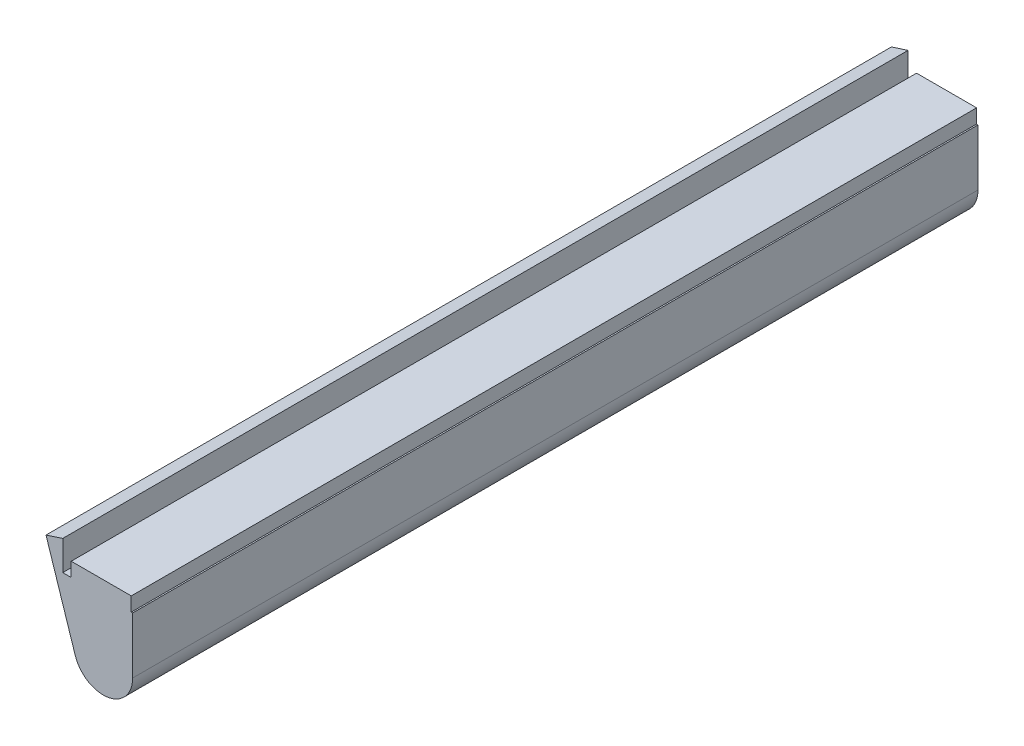
SolidWorks part; units mm, degrees
ref_plane "Front Plane" through (0, 0, 0) normal (0, 0, 1) x (1, 0, 0)
ref_plane "Top Plane" through (0, 0, 0) normal (0, 1, 0) x (1, 0, 0)
ref_plane "Right Plane" through (0, 0, 0) normal (1, 0, 0) x (0, 0, -1)
sketch "Sketch1" plane through (0, 0, 0) normal (0, 0, 1) x (1, 0, 0)
  line L0 (0, -10) -> (0, -5)
  line L1 (0, 266) -> (0, -10) construction
  line L2 (0, -5) -> (21.3, -5)
  line L3 (21.3, 266) -> (21.3, -10) construction
  line L4 (21.3, -5) -> (21.3, -10)
  line L5 (21.3, -10) -> (21.8, -10)
  line L6 (0, -10) -> (-3, -10)
  line L7 (-3, -10) -> (-93, 266)
  line L8 (-5.1329, -3.459) -> (-7.9851, -4.389)
  line L9 (-7.9851, -4.389) -> (-5.8522, -10.9301)
  line L10 (-5.8522, -10.9301) -> (-3, -10)
  line L11 (21.3, -10) -> (6.3, -10)
  line L12 (-5.8522, -10.9301) -> (22.0497, -96.4957)
  line L13 (21.8, -10) -> (21.8, -100)
  line L14 (21.8, -95.7301) -> (22.7507, -95.4201)
  line L15 (21.8, -10) -> (21.8, -30)
  line L16 (21.8, -30) -> (-1.5125, -30)
  line L17 (1.4223, -33.2385) -> (26.3356, -25.1146)
  line L18 (-5.8522, -10.9301) -> (-8.9524, -1.4228)
  line L19 (-8.9524, -1.4228) -> (-3, 0.5182)
  line L20 (-3, 266) -> (-3, -10) construction
  line L21 (-3, 0.5182) -> (-3, -10)
  circle A0 centre (21.8, -95.7301) radius 65.7301
  arc A1 (21.8, -30) -> (1.4223, -33.2385) centre (11.3538, -30) cw
extrude "Boss-Extrude1" add sketch "Sketch1" against normal blind 300
sketch "Sketch2" plane through (0, 0, 0) normal (0, 0, 1) x (1, 0, 0)
  line L0 (21.8, -10) -> (21.8, -30)
  line L1 (-8.9524, -1.4228) -> (0.5209, -30.4742)
  line L2 (-8.9524, -1.4228) -> (1.4223, -33.2385) construction
  line L3 (21.8, -30) -> (21.8, -40.45)
  line L4 (21.8, -40.45) -> (-13.8711, -40.45)
  line L5 (0.5209, -30.4742) -> (7.504, -51.889)
  line L6 (21.8, -10) -> (21.8, -5)
  line L7 (21.8, -5) -> (-7.7859, -5)
  line L8 (-0.5157, -5) -> (-3, -4.7409)
  line L9 (-3, 0.5182) -> (-3, -10) construction
  arc A0 (3.2681, -38.8988) -> (21.8, -35.9537) centre (12.3, -35.9537) ccw
